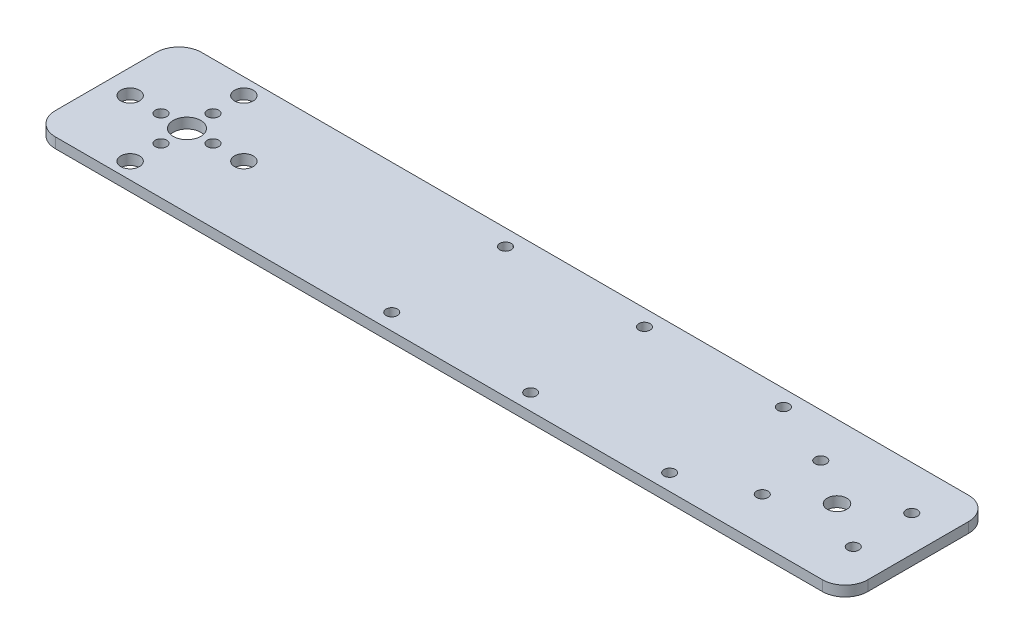
SolidWorks part; units mm, degrees
ref_plane "Front Plane" through (0, 0, 0) normal (0, 0, 1) x (1, 0, 0)
ref_plane "Top Plane" through (0, 0, 0) normal (0, 1, 0) x (1, 0, 0)
ref_plane "Right Plane" through (0, 0, 0) normal (1, 0, 0) x (0, 0, -1)
sketch "Sketch1" plane through (0, 0, 0) normal (0, 1, 0) x (1, 0, 0)
  line L0 (-25, 0) -> (0, 0) construction
  line L1 (-25, 22.5) -> (225, 22.5)
  line L2 (-25, 22.5) -> (-25, -22.5)
  line L3 (-25, -22.5) -> (225, -22.5)
  line L4 (225, 22.5) -> (225, -22.5)
  dimension "D1" = 25
  dimension "D2" = 250
  dimension "D3" = 45
extrude "Boss-Extrude1" add sketch "Sketch1" along normal blind 3.175
sketch "Sketch4" plane through (0, 3.175, 0) normal (0, 1, 0) x (1, 0, 0)
  line L0 (225, 0) -> (-25, 0) construction
  line L1 (225, -22.5) -> (225, 22.5) construction
  line L2 (-25, 22.5) -> (-25, -22.5) construction
  line L3 (200, 22.5) -> (200, -22.5) construction
  line L4 (225, 22.5) -> (-25, 22.5) construction
  line L5 (-25, -22.5) -> (225, -22.5) construction
  circle A0 centre (200, 0) radius 3
  circle A1 centre (186, 9) radius 1.75
  circle A2 centre (214, 9) radius 1.75
  circle A3 centre (214, -9) radius 1.75
  circle A4 centre (186, -9) radius 1.75
  dimension "D1" = 6
  dimension "D5" = 3.5
  dimension "D2" = 25
  dimension "D3" = 14
  dimension "D4" = 9
extrude "Cut-Extrude1" cut sketch "Sketch4" against normal through all
sketch "Sketch5" plane through (0, 3.175, 0) normal (0, 1, 0) x (1, 0, 0)
  circle A0 centre (0, 0) radius 4.25
  dimension "D1" = 8.5
extrude "Cut-Extrude2" cut sketch "Sketch5" against normal through all
sketch "Sketch10" plane through (0, 3.175, 0) normal (0, 1, 0) x (1, 0, 0)
  line L0 (-25, 0) -> (225, 0) construction
  line L1 (-25, -22.5) -> (225, -22.5) construction
  line L2 (225, -22.5) -> (225, 22.5) construction
  line L3 (-25, 22.5) -> (-25, -22.5) construction
  line L4 (80.5, -17.5) -> (123.25, -17.5) construction
  line L5 (123.25, -17.5) -> (166, -17.5) construction
  circle A0 centre (80.5, -17.5) radius 1.75
  circle A1 centre (0, 0) radius 4.25 construction
  circle A2 centre (166, -17.5) radius 1.75
  circle A3 centre (186, -9) radius 1.75 construction
  circle A4 centre (166, 17.5) radius 1.75
  circle A5 centre (80.5, 17.5) radius 1.75
  circle A6 centre (123.25, -17.5) radius 1.75
  circle A7 centre (123.25, 17.5) radius 1.75
  dimension "D3" = 3.5
  dimension "D4" = 20
  dimension "D1" = 80.5
  dimension "D2" = 5
extrude "Cut-Extrude4" cut sketch "Sketch10" against normal through all
fillet "Fillet1" radius 7 4 edges at (-25, 1.5875, 22.5) (-25, 1.5875, -22.5) (225, 1.5875, -22.5) (225, 1.5875, 22.5)
sketch "Sketch11" plane through (0, 3.175, 0) normal (0, 1, 0) x (1, 0, 0)
  line L0 (0, 22.5) -> (0, -22.5) construction
  line L1 (218, 22.5) -> (-18, 22.5) construction
  line L2 (-18, -22.5) -> (218, -22.5) construction
  circle A0 centre (0, 17.5) radius 2.875
  circle A2 centre (0, 0) radius 4.25 construction
  circle A3 centre (17.5, 0) radius 2.875
  circle A4 centre (0, -17.5) radius 2.875
  circle A5 centre (-17.5, 0) radius 2.875
  dimension "D1" = 5.75
  dimension "D2" = 17.5
  dimension "D3" = 4
extrude "Cut-Extrude5" cut sketch "Sketch11" against normal through all
sketch "Sketch12" plane through (0, 3.175, 0) normal (0, 1, 0) x (1, 0, 0)
  circle A0 centre (0, 8) radius 1.75
  circle A1 centre (8, 0) radius 1.75
  circle A2 centre (0, -8) radius 1.75
  circle A3 centre (-8, 0) radius 1.75
  dimension "D1" = 3.5
  dimension "D2" = 8
  dimension "D3" = 4
extrude "Cut-Extrude6" cut sketch "Sketch12" against normal through all
